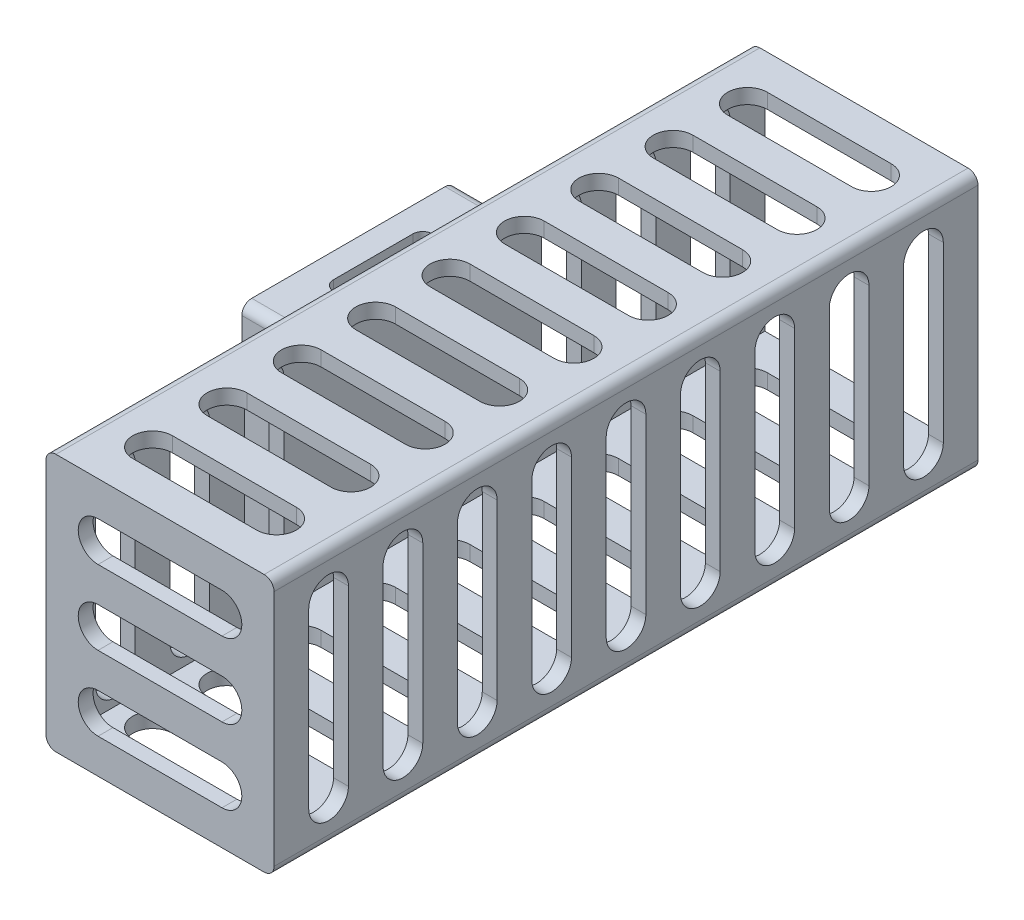
SolidWorks part; units mm, degrees
other "标注1"
sketch "草图13" plane through (-34.5, -21.5, 140) normal (-0.2035, -0.256, 0.945) x (0.0057, 0.9649, 0.2626)
ref_plane "前视基准面" through (0, 0, 0) normal (0, 0, 1) x (1, 0, 0)
ref_plane "上视基准面" through (0, 0, 0) normal (0, 1, 0) x (1, 0, 0)
ref_plane "右视基准面" through (0, 0, 0) normal (1, 0, 0) x (0, 0, -1)
sketch "草图1" plane through (0, 0, 0) normal (0, 0, 1) x (1, 0, 0)
  line L1 (22.5, -19.5) -> (-22.5, -19.5)
  line L2 (22.5, -19.5) -> (22.5, 19.5)
  line L3 (22.5, 19.5) -> (-22.5, 19.5)
  line L4 (-22.5, -19.5) -> (-22.5, 19.5)
  line L5 (22.5, -19.5) -> (-22.5, 19.5) construction
  line L6 (22.5, 19.5) -> (-22.5, -19.5) construction
  point P0 (0, 0)
  dimension "D1" = 45
  dimension "D2" = 39
extrude "拉伸-薄壁1" add sketch "草图1" along normal blind 140 thin thin type one direction wall 2
sketch "草图3" plane through (0, 0, 0) normal (0, 0, -1) x (-1, 0, 0)
  line L1 (-24.5, 21.5) -> (24.5, 21.5)
  line L2 (-24.5, 21.5) -> (-24.5, -21.5)
  line L3 (-24.5, -21.5) -> (24.5, -21.5)
  line L4 (24.5, 21.5) -> (24.5, -21.5)
extrude "凸台-拉伸1" add sketch "草图3" along normal blind 2
sketch "草图4" plane through (-24.5, 0, 0) normal (-1, 0, 0) x (0, 0, 1)
  line L0 (-2, 0) -> (140, 0) construction
  line L1 (-2, -21.5) -> (-2, 21.5) construction
  line L2 (140, 21.5) -> (140, -21.5) construction
  line L3 (140, 21.5) -> (-2, 21.5) construction
  line L4 (90.5, -21.5) -> (47.5, -21.5)
  line L5 (90.5, -21.5) -> (90.5, 21.5)
  line L6 (90.5, 21.5) -> (47.5, 21.5)
  line L7 (47.5, -21.5) -> (47.5, 21.5)
  line L8 (90.5, -21.5) -> (47.5, 21.5) construction
  line L9 (90.5, 21.5) -> (47.5, -21.5) construction
  point P6 (69, 0)
  dimension "D1" = 43
extrude "凸台-拉伸2" add sketch "草图4" along normal blind 10
sketch "草图5" plane through (-34.5, 0, 0) normal (-1, 0, 0) x (0, 0, 1)
  line L0 (47.5, 0) -> (90.5, 0) construction
  line L1 (47.5, 21.5) -> (47.5, -21.5) construction
  line L2 (90.5, -21.5) -> (90.5, 21.5) construction
  line L3 (90.5, 21.5) -> (47.5, 21.5) construction
  line L4 (88.5, -19.5) -> (49.5, -19.5)
  line L5 (88.5, -19.5) -> (88.5, 19.5)
  line L6 (88.5, 19.5) -> (49.5, 19.5)
  line L7 (49.5, -19.5) -> (49.5, 19.5)
  line L8 (88.5, -19.5) -> (49.5, 19.5) construction
  line L9 (88.5, 19.5) -> (49.5, -19.5) construction
  point P6 (69, 0)
  dimension "D1" = 2
  dimension "D2" = 2
extrude "切除-拉伸1" cut sketch "草图5" against normal blind 5
sketch "草图6" plane through (0, 21.5, 0) normal (0, 1, 0) x (1, 0, 0)
  line L0 (-29.5, -47.5) -> (-29.5, -90.5) construction
  line L1 (-34.5, -47.5) -> (-24.5, -47.5) construction
  line L2 (-34.5, -90.5) -> (-24.5, -90.5) construction
  line L3 (-34.5, -90.5) -> (-34.5, -47.5) construction
  line L4 (-24.5, -47.5) -> (-24.5, -90.5) construction
  line L5 (-24.5, -140) -> (-24.5, -90.5) construction
  line L6 (-29.5, -69) -> (-24.5, -69) construction
  line L12 (-24.5, -79) -> (-29.5, -79)
  line L13 (-24.5, -79) -> (-24.5, -59)
  line L14 (-24.5, -59) -> (-29.5, -59)
  line L15 (-29.5, -79) -> (-29.5, -59)
  line L16 (-24.5, -79) -> (-29.5, -59) construction
  line L17 (-24.5, -59) -> (-29.5, -79) construction
  point P15 (-27, -69)
  point P16 (-27, -69)
  dimension "D1" = 5
  dimension "D2" = 20
extrude "切除-拉伸2" cut sketch "草图6" against normal through all
sketch "草图8" plane through (-24.5, 0, 0) normal (-1, 0, 0) x (0, 0, 1)
  line L0 (59, 0) -> (79, 0) construction
  line L1 (59, -21.5) -> (59, 21.5) construction
  line L2 (79, -21.5) -> (79, 21.5) construction
  line L4 (79, -4) -> (59, -4)
  line L5 (79, -4) -> (79, 4)
  line L6 (79, 4) -> (59, 4)
  line L7 (59, -4) -> (59, 4)
  line L8 (79, -4) -> (59, 4) construction
  line L9 (79, 4) -> (59, -4) construction
  point P6 (69, 0)
  dimension "D1" = 8
extrude "凸台-拉伸4" add sketch "草图8" along normal up to surface (5 mm away) up to face at (-29.5, 0, 54.25)
sketch "草图9" plane through (-29.5, 0, 0) normal (-1, 0, 0) x (0, 0, 1)
  line L0 (59, 11.75) -> (79, 11.75) construction
  line L1 (59, 4) -> (59, 19.5) construction
  line L2 (79, 4) -> (79, 21.5) construction
  line L3 (59, 19.5) -> (49.5, 19.5) construction
  line L4 (83.75, 4) -> (54.25, 4)
  line L5 (83.75, 4) -> (83.75, 19.5)
  line L6 (83.75, 19.5) -> (54.25, 19.5)
  line L7 (54.25, 4) -> (54.25, 19.5)
  line L8 (83.75, 4) -> (54.25, 19.5) construction
  line L9 (83.75, 19.5) -> (54.25, 4) construction
  line L10 (59, -11.75) -> (79, -11.75) construction
  line L11 (59, -19.5) -> (59, -4) construction
  line L12 (79, -21.5) -> (79, -4) construction
  line L13 (49.5, 19.5) -> (49.5, -19.5) construction
  line L14 (83.75, -19.5) -> (54.25, -19.5)
  line L15 (83.75, -19.5) -> (83.75, -4)
  line L16 (83.75, -4) -> (54.25, -4)
  line L17 (54.25, -19.5) -> (54.25, -4)
  line L18 (83.75, -19.5) -> (54.25, -4) construction
  line L19 (83.75, -4) -> (54.25, -19.5) construction
  point P6 (69, 11.75)
  point P19 (69, -11.75)
  dimension "D1" = 8
  dimension "D2" = 4.75
extrude "切除-拉伸3" cut sketch "草图9" against normal blind 5
sketch "草图10" plane through (0, -4, 0) normal (0, -1, 0) x (1, 0, 0)
  line L0 (-24.5, 69) -> (-29.5, 69) construction
  line L1 (-24.5, 79) -> (-24.5, 59) construction
  line L2 (-29.5, 59) -> (-29.5, 79) construction
  circle A0 centre (-27, 78.5) radius 1.5
  circle A1 centre (-27, 59.5) radius 1.5
  dimension "D1" = 3
  dimension "D2" = 19
extrude "切除-拉伸4" cut sketch "草图10" against normal blind 3
sketch "草图11" plane through (0, 4, 0) normal (0, 1, 0) x (1, 0, 0)
  circle A0 centre (-27, -59.5) radius 1.5
  circle A1 centre (-27, -78.5) radius 1.5
  dimension "D1" = 3
  dimension "D2" = 3
extrude "切除-拉伸5" cut sketch "草图11" against normal blind 3
fillet "圆角1" radius 2 8 edges at (-29.5, -20.5, 59) (-29.5, -20.5, 79) (-24.5, -20.5, 79) (-24.5, -20.5, 59) (-24.5, 20.5, 59) (-24.5, 20.5, 79) (-29.5, 20.5, 79) (-29.5, 20.5, 59)
sketch "草图12" plane through (-29.5, 0, 0) normal (-1, 0, 0) x (0, 0, 1)
  line L0 (83.75, 4) -> (54.25, 4) construction
  line L1 (74, -4) -> (64, -4)
  line L2 (74, -4) -> (74, 4)
  line L3 (74, 4) -> (64, 4)
  line L4 (64, -4) -> (64, 4)
  line L5 (74, -4) -> (64, 4) construction
  line L6 (74, 4) -> (64, -4) construction
  point P0 (69, 0)
  dimension "D1" = 10
  dimension "D2" = 8
extrude "切除-拉伸6" cut sketch "草图12" against normal up to surface (5 mm away) up to face at (-24.5, 16.125, 69)
fillet "圆角2" radius 2 4 edges at (-32, 19.5, 49.5) (-32, -19.5, 49.5) (-32, -19.5, 88.5) (-32, 19.5, 88.5)
fillet "圆角3" radius 2 4 edges at (-29.5, -21.5, 47.5) (-29.5, -21.5, 90.5) (-29.5, 21.5, 90.5) (-29.5, 21.5, 47.5)
fillet "圆角4" radius 2 8 edges at (-27, 4, 83.75) (-27, 19.5, 54.25) (-27, 4, 54.25) (-27, 19.5, 83.75) (-27, -4, 54.25) (-27, -19.5, 83.75) (-27, -19.5, 54.25) (-27, -4, 83.75)
sketch "草图14" plane through (0, 0, 140) normal (0, 0, 1) x (1, 0, 0)
  line L1 (-24.5, 21.5) -> (24.5, 21.5)
  line L2 (-24.5, 21.5) -> (-24.5, -21.5)
  line L3 (-24.5, -21.5) -> (24.5, -21.5)
  line L4 (24.5, 21.5) -> (24.5, -21.5)
extrude "切除-拉伸7" cut sketch "草图14" against normal through all
sketch "草图15" plane through (-24.5, 0, 0) normal (1, 0, 0) x (0, 0, -1)
  line L0 (-90.5, 0) -> (-47.5, 0) construction
  line L1 (-90.5, -19.5) -> (-90.5, 19.5) construction
  line L2 (-47.5, 19.5) -> (-47.5, -19.5) construction
  line L4 (2, -26) -> (-140, -26)
  line L5 (2, -26) -> (2, 26)
  line L6 (2, 26) -> (-140, 26)
  line L7 (-140, -26) -> (-140, 26)
  line L8 (2, -26) -> (-140, 26) construction
  line L9 (2, 26) -> (-140, -26) construction
  point P6 (-69, 0)
  dimension "D1" = 52
  dimension "D2" = 142
extrude "凸台-拉伸5" add sketch "草图15" along normal blind 46
sketch "草图16" plane through (0, 0, -2) normal (0, 0, -1) x (-1, 0, 0)
  line L0 (-21.5, 0) -> (24.5, 0) construction
  line L1 (-21.5, -26) -> (-21.5, 26) construction
  line L2 (24.5, 19.5) -> (24.5, -19.5) construction
  line L3 (-21.5, 26) -> (24.5, 26) construction
  line L4 (21.5, -23) -> (-18.5, -23)
  line L5 (21.5, -23) -> (21.5, 23)
  line L6 (21.5, 23) -> (-18.5, 23)
  line L7 (-18.5, -23) -> (-18.5, 23)
  line L8 (21.5, -23) -> (-18.5, 23) construction
  line L9 (21.5, 23) -> (-18.5, -23) construction
  point P6 (1.5, 0)
  dimension "D1" = 3
  dimension "D2" = 3
extrude "切除-拉伸8" cut sketch "草图16" against normal offset from surface (139 mm away) 3 up to face at (-1.5, 0, 140)
sketch "草图17" plane through (0, -26, 0) normal (0, -1, 0) x (1, 0, 0)
  line L0 (-24.5, 69) -> (21.5, 69) construction
  line L1 (-24.5, 140) -> (-24.5, -2) construction
  line L2 (21.5, 140) -> (21.5, -2) construction
  line L3 (-1.5, 140) -> (-1.5, -2) construction
  line L4 (21.5, 140) -> (-24.5, 140) construction
  line L5 (21.5, -2) -> (-24.5, -2) construction
  line L11 (-14, 69) -> (11, 69) construction
  line L14 (-14, 73) -> (11, 73)
  line L17 (-14, 65) -> (11, 65)
  line L20 (-14, 80) -> (11, 80)
  line L23 (-14, 88) -> (11, 88)
  line L26 (-14, 84) -> (11, 84) construction
  line L29 (-14, 95) -> (11, 95)
  line L32 (-14, 103) -> (11, 103)
  line L34 (-14, 99) -> (11, 99) construction
  line L35 (-14, 110) -> (11, 110)
  line L36 (-14, 118) -> (11, 118)
  line L37 (-14, 114) -> (11, 114) construction
  line L38 (-14, 125) -> (11, 125)
  line L39 (-14, 133) -> (11, 133)
  line L40 (-14, 129) -> (11, 129) construction
  line L41 (-14, 50) -> (11, 50)
  line L42 (-14, 58) -> (11, 58)
  line L43 (-14, 54) -> (11, 54) construction
  line L44 (-14, 35) -> (11, 35)
  line L45 (-14, 43) -> (11, 43)
  line L46 (-14, 39) -> (11, 39) construction
  line L47 (-14, 20) -> (11, 20)
  line L48 (-14, 28) -> (11, 28)
  line L49 (-14, 24) -> (11, 24) construction
  line L50 (-14, 5) -> (11, 5)
  line L51 (-14, 13) -> (11, 13)
  line L52 (-14, 9) -> (11, 9) construction
  arc A20 (-14, 73) -> (-14, 65) centre (-14, 69) ccw
  arc A21 (11, 65) -> (11, 73) centre (11, 69) ccw
  arc A22 (-14, 88) -> (-14, 80) centre (-14, 84) ccw
  arc A23 (11, 80) -> (11, 88) centre (11, 84) ccw
  arc A24 (-14, 103) -> (-14, 95) centre (-14, 99) ccw
  arc A25 (11, 95) -> (11, 103) centre (11, 99) ccw
  arc A26 (-14, 118) -> (-14, 110) centre (-14, 114) ccw
  arc A27 (11, 110) -> (11, 118) centre (11, 114) ccw
  arc A28 (-14, 133) -> (-14, 125) centre (-14, 129) ccw
  arc A29 (11, 125) -> (11, 133) centre (11, 129) ccw
  arc A30 (-14, 58) -> (-14, 50) centre (-14, 54) ccw
  arc A31 (11, 50) -> (11, 58) centre (11, 54) ccw
  arc A32 (-14, 43) -> (-14, 35) centre (-14, 39) ccw
  arc A33 (11, 35) -> (11, 43) centre (11, 39) ccw
  arc A34 (-14, 28) -> (-14, 20) centre (-14, 24) ccw
  arc A35 (11, 20) -> (11, 28) centre (11, 24) ccw
  arc A36 (-14, 13) -> (-14, 5) centre (-14, 9) ccw
  arc A37 (11, 5) -> (11, 13) centre (11, 9) ccw
  point P14 (-1.5, 69)
  point P23 (-1.5, 84)
  point P30 (-1.5, 99)
  point P37 (-1.5, 114)
  point P44 (-1.5, 129)
  point P51 (-1.5, 54)
  point P58 (-1.5, 39)
  point P65 (-1.5, 24)
  point P72 (-1.5, 9)
  dimension "D3" = 25
  dimension "D1" = 4
  dimension "D2" = 0
  dimension "D4" = 5
  dimension "D5" = 5
extrude "切除-拉伸9" cut sketch "草图17" against normal through all
sketch "草图18" plane through (21.5, 0, 0) normal (1, 0, 0) x (0, 0, -1)
  line L0 (-140, 0) -> (2, 0) construction
  line L1 (-140, 26) -> (-140, -26) construction
  line L2 (2, -26) -> (2, 26) construction
  line L8 (-69, 26) -> (-69, -26) construction
  line L11 (2, 26) -> (-140, 26) construction
  line L14 (-140, -26) -> (2, -26) construction
  line L17 (-69, 17.5) -> (-69, -17.5) construction
  line L20 (-65, 17.5) -> (-65, -17.5)
  line L23 (-73, 17.5) -> (-73, -17.5)
  line L26 (-58, 17.5) -> (-58, -17.5)
  line L29 (-50, 17.5) -> (-50, -17.5)
  line L31 (-54, 17.5) -> (-54, -17.5) construction
  line L32 (-43, 17.5) -> (-43, -17.5)
  line L33 (-35, 17.5) -> (-35, -17.5)
  line L34 (-39, 17.5) -> (-39, -17.5) construction
  line L35 (-28, 17.5) -> (-28, -17.5)
  line L36 (-20, 17.5) -> (-20, -17.5)
  line L37 (-24, 17.5) -> (-24, -17.5) construction
  line L38 (-13, 17.5) -> (-13, -17.5)
  line L39 (-5, 17.5) -> (-5, -17.5)
  line L40 (-9, 17.5) -> (-9, -17.5) construction
  line L41 (-88, 17.5) -> (-88, -17.5)
  line L42 (-80, 17.5) -> (-80, -17.5)
  line L43 (-84, 17.5) -> (-84, -17.5) construction
  line L44 (-103, 17.5) -> (-103, -17.5)
  line L45 (-95, 17.5) -> (-95, -17.5)
  line L46 (-99, 17.5) -> (-99, -17.5) construction
  line L47 (-118, 17.5) -> (-118, -17.5)
  line L48 (-110, 17.5) -> (-110, -17.5)
  line L49 (-114, 17.5) -> (-114, -17.5) construction
  line L50 (-133, 17.5) -> (-133, -17.5)
  line L51 (-125, 17.5) -> (-125, -17.5)
  line L52 (-129, 17.5) -> (-129, -17.5) construction
  arc A20 (-65, 17.5) -> (-73, 17.5) centre (-69, 17.5) ccw
  arc A21 (-73, -17.5) -> (-65, -17.5) centre (-69, -17.5) ccw
  arc A22 (-50, 17.5) -> (-58, 17.5) centre (-54, 17.5) ccw
  arc A23 (-58, -17.5) -> (-50, -17.5) centre (-54, -17.5) ccw
  arc A24 (-35, 17.5) -> (-43, 17.5) centre (-39, 17.5) ccw
  arc A25 (-43, -17.5) -> (-35, -17.5) centre (-39, -17.5) ccw
  arc A26 (-20, 17.5) -> (-28, 17.5) centre (-24, 17.5) ccw
  arc A27 (-28, -17.5) -> (-20, -17.5) centre (-24, -17.5) ccw
  arc A28 (-5, 17.5) -> (-13, 17.5) centre (-9, 17.5) ccw
  arc A29 (-13, -17.5) -> (-5, -17.5) centre (-9, -17.5) ccw
  arc A30 (-80, 17.5) -> (-88, 17.5) centre (-84, 17.5) ccw
  arc A31 (-88, -17.5) -> (-80, -17.5) centre (-84, -17.5) ccw
  arc A32 (-95, 17.5) -> (-103, 17.5) centre (-99, 17.5) ccw
  arc A33 (-103, -17.5) -> (-95, -17.5) centre (-99, -17.5) ccw
  arc A34 (-110, 17.5) -> (-118, 17.5) centre (-114, 17.5) ccw
  arc A35 (-118, -17.5) -> (-110, -17.5) centre (-114, -17.5) ccw
  arc A36 (-125, 17.5) -> (-133, 17.5) centre (-129, 17.5) ccw
  arc A37 (-133, -17.5) -> (-125, -17.5) centre (-129, -17.5) ccw
  point P14 (-69, 0)
  point P22 (-54, 0)
  point P29 (-39, 0)
  point P36 (-24, 0)
  point P43 (-9, 0)
  point P51 (-84, 0)
  point P58 (-99, 0)
  point P65 (-114, 0)
  point P72 (-129, 0)
  dimension "D3" = 0
  dimension "D1" = 4
  dimension "D2" = 35
  dimension "D4" = 5
  dimension "D5" = 5
extrude "切除-拉伸10" cut sketch "草图18" against normal blind 10
sketch "草图19" plane through (-24.5, 0, 0) normal (-1, 0, 0) x (0, 0, 1)
  line L0 (-2, 0) -> (140, 0) construction
  line L1 (-2, -26) -> (-2, 26) construction
  line L2 (140, 26) -> (140, -26) construction
  line L3 (69, 26) -> (69, -26) construction
  line L8 (-2, 26) -> (140, 26) construction
  line L11 (140, -26) -> (-2, -26) construction
  line L18 (95, 17.5) -> (95, -17.5)
  line L19 (103, 17.5) -> (103, -17.5)
  line L20 (99, 17.5) -> (99, -17.5) construction
  line L21 (110, 17.5) -> (110, -17.5)
  line L22 (118, 17.5) -> (118, -17.5)
  line L23 (114, 17.5) -> (114, -17.5) construction
  line L24 (125, 17.5) -> (125, -17.5)
  line L25 (133, 17.5) -> (133, -17.5)
  line L26 (129, 17.5) -> (129, -17.5) construction
  line L30 (35, 17.5) -> (35, -17.5)
  line L31 (43, 17.5) -> (43, -17.5)
  line L32 (39, 17.5) -> (39, -17.5) construction
  line L33 (20, 17.5) -> (20, -17.5)
  line L34 (28, 17.5) -> (28, -17.5)
  line L35 (24, 17.5) -> (24, -17.5) construction
  line L36 (5, 17.5) -> (5, -17.5)
  line L37 (13, 17.5) -> (13, -17.5)
  line L38 (9, 17.5) -> (9, -17.5) construction
  arc A10 (103, 17.5) -> (95, 17.5) centre (99, 17.5) ccw
  arc A11 (95, -17.5) -> (103, -17.5) centre (99, -17.5) ccw
  arc A12 (118, 17.5) -> (110, 17.5) centre (114, 17.5) ccw
  arc A13 (110, -17.5) -> (118, -17.5) centre (114, -17.5) ccw
  arc A14 (133, 17.5) -> (125, 17.5) centre (129, 17.5) ccw
  arc A15 (125, -17.5) -> (133, -17.5) centre (129, -17.5) ccw
  arc A18 (43, 17.5) -> (35, 17.5) centre (39, 17.5) ccw
  arc A19 (35, -17.5) -> (43, -17.5) centre (39, -17.5) ccw
  arc A20 (28, 17.5) -> (20, 17.5) centre (24, 17.5) ccw
  arc A21 (20, -17.5) -> (28, -17.5) centre (24, -17.5) ccw
  arc A22 (13, 17.5) -> (5, 17.5) centre (9, 17.5) ccw
  arc A23 (5, -17.5) -> (13, -17.5) centre (9, -17.5) ccw
  point P30 (99, 0)
  point P37 (114, 0)
  point P44 (129, 0)
  point P58 (39, 0)
  point P65 (24, 0)
  point P72 (9, 0)
extrude "切除-拉伸11" cut sketch "草图19" against normal blind 10
fillet "圆角5" radius 2 4 edges at (-24.5, -26, 69) (21.5, -26, 69) (21.5, 26, 69) (-24.5, 26, 69)
sketch "草图20" plane through (0, 0, 140) normal (0, 0, 1) x (1, 0, 0)
  line L0 (-24.5, 0) -> (21.5, 0) construction
  line L1 (-24.5, 24) -> (-24.5, -24) construction
  line L2 (21.5, 24) -> (21.5, -24) construction
  line L3 (-1.5, 26) -> (-1.5, -26) construction
  line L4 (19.5, 26) -> (-22.5, 26) construction
  line L5 (19.5, -26) -> (-22.5, -26) construction
  line L6 (-14, 0) -> (11, 0) construction
  line L7 (-14, 4) -> (11, 4)
  line L8 (-14, -4) -> (11, -4)
  line L9 (-14, 11) -> (11, 11)
  line L10 (-14, 19) -> (11, 19)
  line L11 (-14, 15) -> (11, 15) construction
  line L12 (-14, -19) -> (11, -19)
  line L13 (-14, -11) -> (11, -11)
  line L14 (-14, -15) -> (11, -15) construction
  arc A0 (-14, 4) -> (-14, -4) centre (-14, 0) ccw
  arc A1 (11, -4) -> (11, 4) centre (11, 0) ccw
  arc A2 (-14, 19) -> (-14, 11) centre (-14, 15) ccw
  arc A3 (11, 11) -> (11, 19) centre (11, 15) ccw
  arc A4 (-14, -11) -> (-14, -19) centre (-14, -15) ccw
  arc A5 (11, -19) -> (11, -11) centre (11, -15) ccw
  point P14 (-1.5, 0)
  point P22 (-1.5, 15)
  point P29 (-1.5, -15)
  dimension "D1" = 4
  dimension "D2" = 25
  dimension "D3" = 0
  dimension "D4" = 2
  dimension "D5" = 2
extrude "切除-拉伸12" cut sketch "草图20" against normal blind 10
